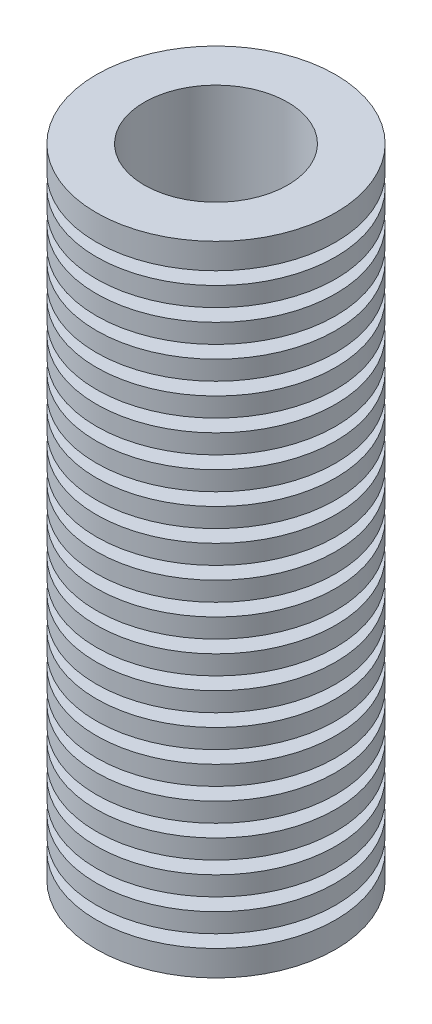
SolidWorks part; units mm, degrees
material "6061 Alloy"
ref_plane "Front Plane" through (0, 0, 0) normal (0, 0, 1) x (1, 0, 0)
ref_plane "Top Plane" through (0, 0, 0) normal (0, 1, 0) x (1, 0, 0)
ref_plane "Right Plane" through (0, 0, 0) normal (1, 0, 0) x (0, 0, -1)
sketch "Sketch1" plane through (0, 0, 0) normal (0, 1, 0) x (1, 0, 0)
  circle A0 centre (0, 0) radius 37.5
  dimension "D1" = 75
extrude "Boss-Extrude1" add sketch "Sketch1" along normal mid plane 200
sketch "Sketch2" plane through (0, 0, 0) normal (0, 1, 0) x (1, 0, 0)
  circle A0 centre (0, 0) radius 22.5
  circle A1 centre (0, 0) radius 37.5 construction
  dimension "D1" = 15
extrude "Cut-Extrude1" cut sketch "Sketch2" against normal through all both and the other way through all
ref_axis "Axis1" through (0, -110, 0) along (0, 1, 0)
sketch "Sketch3" plane through (0, 0, 0) normal (0, 0, 1) x (1, 0, 0)
  line L0 (37.5, -100) -> (37.5, 100) construction
  line L1 (37.5, 92) -> (26.5, 92)
  line L2 (37.5, 92) -> (37.5, 88)
  line L3 (37.5, 88) -> (26.5, 88)
  line L4 (26.5, 92) -> (26.5, 88)
  line L6 (37.5, 100) -> (-37.5, 100) construction
  dimension "D1" = 4
  dimension "D2" = 4
  dimension "D3" = 8
revolve "Cut-Revolve1" cut sketch "Sketch3" angle 360 about axis through (0, -110, 0) along (0, 1, 0)
pattern_linear "LPattern1" count 19 spacing 10 along (0, -1, 0) of "Cut-Revolve1"
